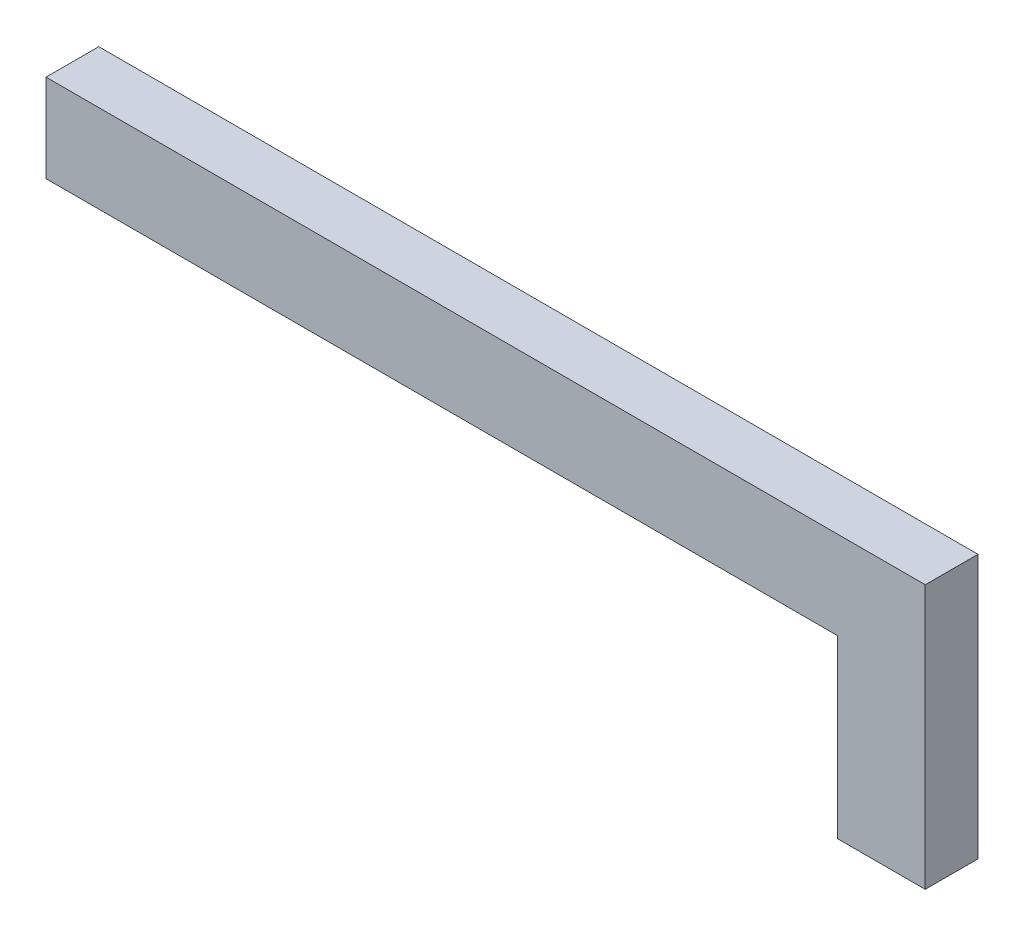
SolidWorks part; units mm, degrees
ref_plane "Front Plane" through (0, 0, 0) normal (0, 0, 1) x (1, 0, 0)
ref_plane "Top Plane" through (0, 0, 0) normal (0, 1, 0) x (1, 0, 0)
ref_plane "Right Plane" through (0, 0, 0) normal (1, 0, 0) x (0, 0, -1)
sketch "Sketch1" plane through (0, 0, 0) normal (0, 0, 1) x (1, 0, 0)
  line L1 (20, -2.5) -> (-25, -2.5)
  line L2 (25, -2.5) -> (25, 2.5)
  line L3 (25, 2.5) -> (-25, 2.5)
  line L4 (-25, -2.5) -> (-25, 2.5)
  line L5 (0, 0) -> (-25, 2.5) construction
  line L6 (25, 2.5) -> (-25, -2.5) construction
  line L8 (20, -2.5) -> (20, -12.5)
  line L9 (20, -12.5) -> (25, -12.5)
  line L10 (25, -2.5) -> (25, -12.5)
  point P0 (0, 0)
  dimension "D1" = 5
  dimension "D2" = 50
  dimension "D3" = 5
  dimension "D4" = 10
extrude "Boss-Extrude1" add sketch "Sketch1" along normal blind 3
